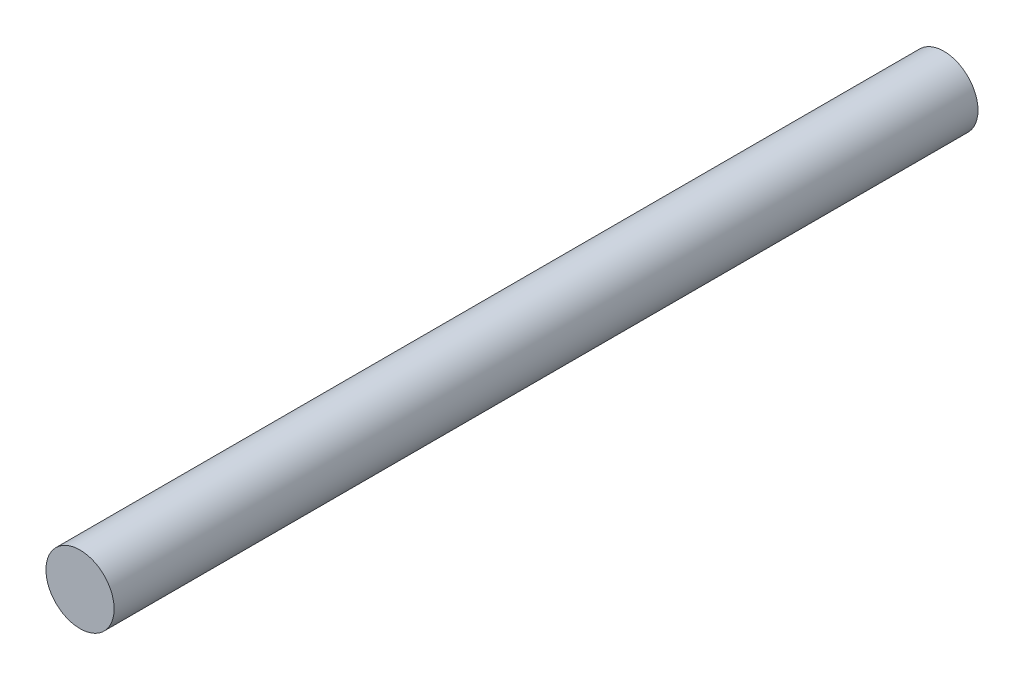
SolidWorks part; units mm, degrees
ref_plane "Front Plane" through (0, 0, 0) normal (0, 0, 1) x (1, 0, 0)
ref_plane "Top Plane" through (0, 0, 0) normal (0, 1, 0) x (1, 0, 0)
ref_plane "Right Plane" through (0, 0, 0) normal (1, 0, 0) x (0, 0, -1)
sketch "Sketch1" plane through (0, 0, 0) normal (0, 0, 1) x (1, 0, 0)
  circle A0 centre (0, 0) radius 0.75
  dimension "D1" = 1.5
extrude "Boss-Extrude1" add sketch "Sketch1" along normal blind 19
